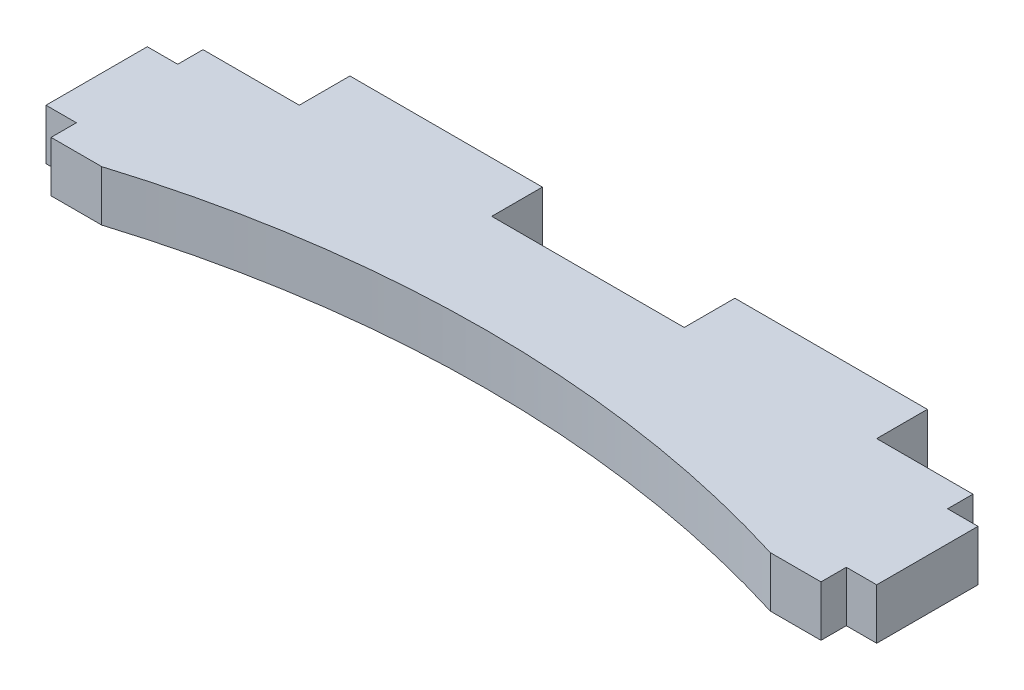
SolidWorks part; units mm, degrees
ref_plane "Front Plane" through (0, 0, 0) normal (0, 0, 1) x (1, 0, 0)
ref_plane "Top Plane" through (0, 0, 0) normal (0, 1, 0) x (1, 0, 0)
ref_plane "Right Plane" through (0, 0, 0) normal (1, 0, 0) x (0, 0, -1)
sketch "Sketch1" plane through (0, 0, 0) normal (0, 1, 0) x (1, 0, 0)
  line L0 (-41, -5) -> (-41, 5)
  line L1 (38, -7.5) -> (-38, -7.5) construction
  line L2 (38, -7.5) -> (38, 7.5) construction
  line L3 (38, 7.5) -> (-38, 7.5) construction
  line L4 (-38, -7.5) -> (-38, 7.5) construction
  line L5 (-41, -5) -> (-38, -5)
  line L6 (38, 0) -> (-38, 0) construction
  line L7 (-41, 5) -> (-38, 5)
  line L8 (-38, 5) -> (-38, 7.5)
  line L9 (-38, 7.5) -> (-28.5, 7.5)
  line L10 (-28.5, 7.5) -> (-28.5, 12.5)
  line L11 (-28.5, 12.5) -> (-9.5, 12.5)
  line L12 (-9.5, 12.5) -> (-9.5, 7.5)
  line L13 (-9.5, 7.5) -> (0, 7.5)
  line L14 (-38, -5) -> (-38, -7.5)
  line L16 (0, 7.5) -> (0, -7.5)
  line L17 (-19, 12.5) -> (-19, 0) construction
  line L18 (-38, -7.5) -> (0, -7.5)
  point P16 (-41, 0)
  point P20 (0, -7.5)
  point P104 (0, 0)
  dimension "D1" = 76
  dimension "D2" = 3
  dimension "D3" = 5
  dimension "D6" = 19
  dimension "D4" = 10
  dimension "D5" = 15
  dimension "D7" = 19
extrude "Boss-Extrude1" add sketch "Sketch1" along normal blind 5
mirror "Mirror1" about plane through (0, 5, -7.5) normal (-1, 0, 0) of "Boss-Extrude1"
sketch "Sketch4" plane through (0, 5, 0) normal (0, 1, 0) x (1, 0, 0)
  line L0 (-38, -7.5) -> (38, -7.5) construction
  line L1 (-33, -7.5) -> (33, -7.5)
  line L2 (9.5, 7.5) -> (-9.5, 7.5) construction
  arc A1 (-33, -7.5) -> (33, -7.5) centre (0, -113.9) cw
  point P4 (0, -2.5)
  dimension "D1" = 5
  dimension "D2" = 10
extrude "Cut-Extrude1" cut sketch "Sketch4" against normal through all
equation "\"3mm akryyli\"= 3mm"
equation "\"5mm akryyli\"= 5mm"
equation "\"D2@Sketch1\"=\"3mm akryyli\""
equation "\"D3@Sketch1\"=\"5mm akryyli\""
